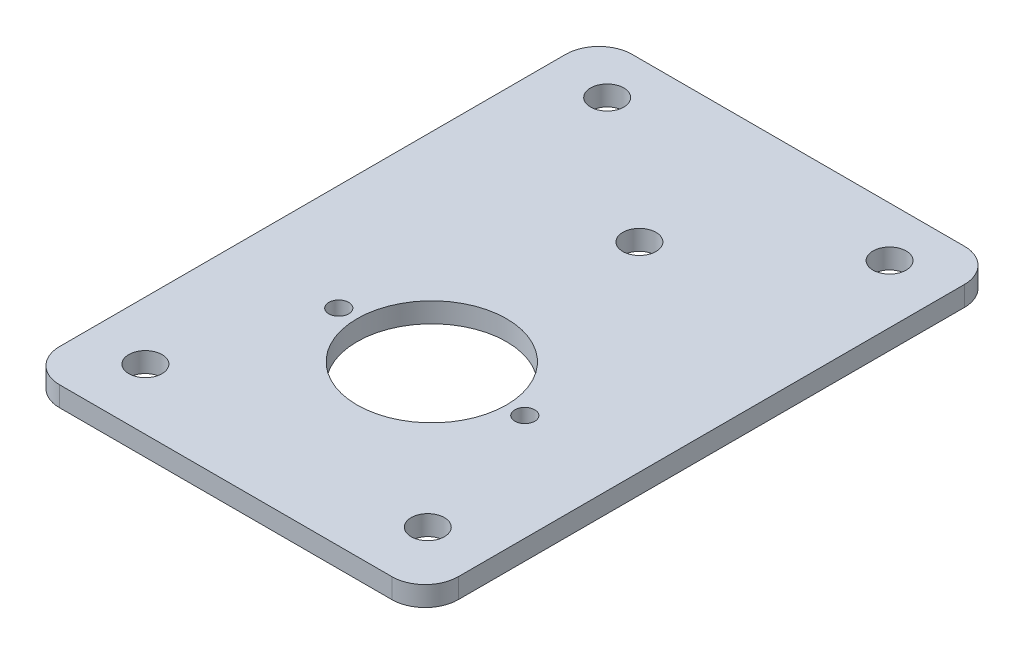
SolidWorks part; units mm, degrees
ref_plane "Front Plane" through (0, 0, 0) normal (0, 0, 1) x (1, 0, 0)
ref_plane "Top Plane" through (0, 0, 0) normal (0, 1, 0) x (1, 0, 0)
ref_plane "Right Plane" through (0, 0, 0) normal (1, 0, 0) x (0, 0, -1)
sketch "Sketch1" plane through (0, 0, 0) normal (0, 1, 0) x (1, 0, 0)
  line L1 (-60, -90) -> (60, -90)
  line L2 (-60, -90) -> (-60, 90)
  line L3 (-60, 90) -> (60, 90)
  line L4 (60, -90) -> (60, 90)
  line L5 (-60, -90) -> (60, 90) construction
  line L6 (-60, 90) -> (60, -90) construction
  point P0 (0, 0)
  dimension "D1" = 180
  dimension "D2" = 120
extrude "Boss-Extrude1" add sketch "Sketch1" along normal blind 6
sketch "Sketch2" plane through (0, 6, 0) normal (0, 1, 0) x (1, 0, 0)
  line L0 (-60, -90) -> (60, -90) construction
  line L2 (-42.5, 75) -> (42.5, 75) construction
  line L3 (60, 90) -> (-60, 90) construction
  circle A0 centre (-42.5, 75) radius 5
  circle A1 centre (42.5, 75) radius 5
  circle A2 centre (-42.5, -64) radius 5
  circle A3 centre (42.5, -64) radius 5
  circle A4 centre (0, 42.2) radius 5
  point P10 (0, 75)
  dimension "D1" = 26
  dimension "D5" = 85
  dimension "D6" = 10
  dimension "D7" = 10
  dimension "D9" = 10
  dimension "D3" = 15
extrude "Cut-Extrude1" cut sketch "Sketch2" against normal blind 6
sketch "Sketch4" plane through (0, 6, 0) normal (0, 1, 0) x (1, 0, 0)
  circle A0 centre (0, -20.3) radius 22.5
  circle A1 centre (0, 42.2) radius 5 construction
  circle A2 centre (-28, -20.3) radius 3
  circle A3 centre (28, -20.3) radius 3
  dimension "D3" = 45
  dimension "D4" = 6
  dimension "D1" = 0
  dimension "D2" = 62.5
  dimension "D5" = 28
  dimension "D6" = 28
extrude "Cut-Extrude3" cut sketch "Sketch4" against normal blind 10
sketch "Sketch5" plane through (0, 6, 0) normal (0, 1, 0) x (1, 0, 0)
  line L0 (60, -90) -> (60, 90) construction
  line L1 (-60, -90) -> (60, -90)
  line L2 (-60, -90) -> (-60, -82.302)
  line L3 (-60, -82.302) -> (60, -82.302)
  line L4 (60, -90) -> (60, -82.302)
extrude "Cut-Extrude4" cut sketch "Sketch5" against normal blind 10
fillet "Fillet1" radius 10 4 edges at (60, 3, -90) (-60, 3, -90) (60, 3, 82.302) (-60, 3, 82.302)
